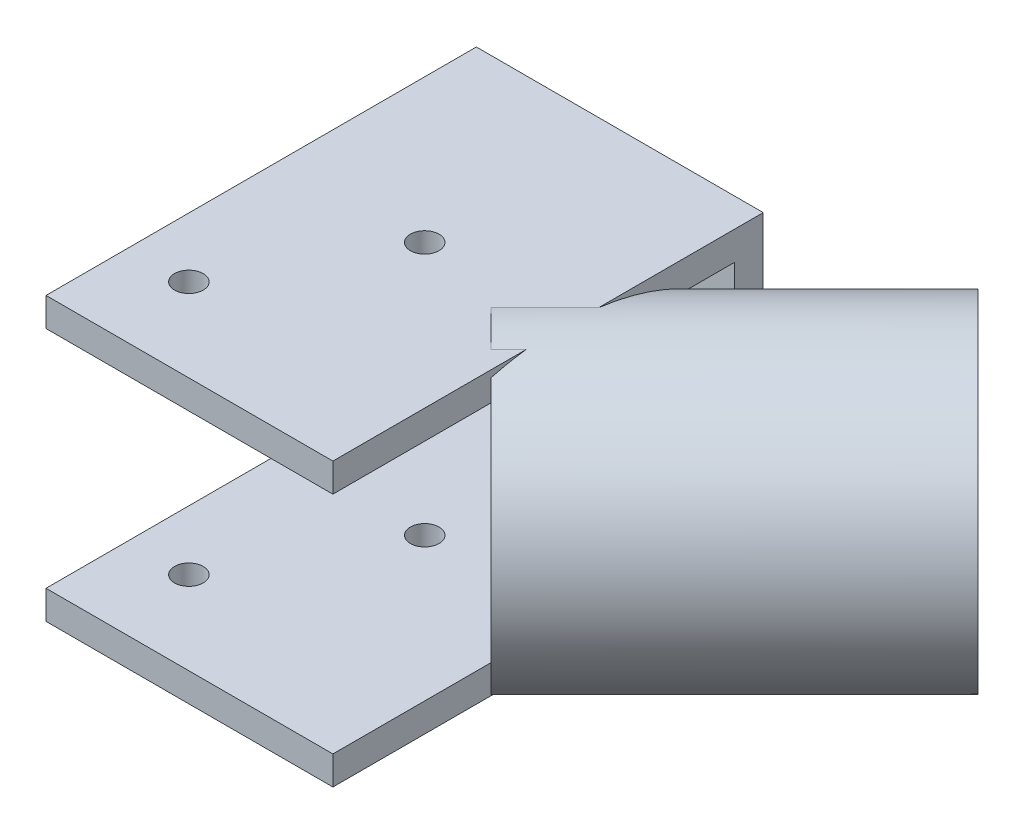
SolidWorks part; units mm, degrees
ref_plane "Plan de face" through (0, 0, 0) normal (0, 0, 1) x (1, 0, 0)
ref_plane "Plan de dessus" through (0, 0, 0) normal (0, 1, 0) x (1, 0, 0)
ref_plane "Plan de droite" through (0, 0, 0) normal (1, 0, 0) x (0, 0, -1)
sketch "Esquisse1" plane through (0, 0, 0) normal (0, 0, 1) x (1, 0, 0)
  line L0 (0, 24.6) -> (50, 24.6) construction
  line L1 (0, 0) -> (50, 0)
  line L2 (0, 0) -> (0, 49.2)
  line L3 (0, 49.2) -> (50, 49.2)
  line L4 (50, 0) -> (50, 49.2)
  dimension "D1" = 50
  dimension "D2" = 24.6
  dimension "D3" = 24.6
extrude "Boss.-Extru.1" add sketch "Esquisse1" along normal blind 5
sketch "Esquisse4" plane through (0, 0, 5) normal (0, 0, 1) x (1, 0, 0)
  line L0 (50, 0) -> (50, 49.2) construction
  line L1 (0, 49.2) -> (50, 49.2)
  line L2 (0, 49.2) -> (0, 44.2)
  line L3 (0, 44.2) -> (50, 44.2)
  line L4 (50, 49.2) -> (50, 44.2)
  line L6 (0, 0) -> (50, 0)
  line L7 (0, 0) -> (0, 5)
  line L8 (0, 5) -> (50, 5)
  line L9 (50, 0) -> (50, 5)
  dimension "D1" = 5
  dimension "D2" = 5
extrude "Boss.-Extru.3" add sketch "Esquisse4" along normal blind 70
sketch "Esquisse5" plane through (0, 0, 5) normal (0, 0, 1) x (1, 0, 0)
  line L0 (0, 5) -> (50, 44.2) construction
  line L1 (50, 5) -> (0, 44.2) construction
  line L3 (40.7, 8.9) -> (9.3, 8.9) construction
  line L4 (40.7, 8.9) -> (40.7, 40.3) construction
  line L5 (40.7, 40.3) -> (9.3, 40.3) construction
  line L6 (9.3, 8.9) -> (9.3, 40.3) construction
  line L7 (40.7, 8.9) -> (9.3, 40.3) construction
  line L8 (40.7, 40.3) -> (9.3, 8.9) construction
  circle A0 centre (25, 24.6) radius 10
  circle A5 centre (9.3, 8.9) radius 1.25
  circle A6 centre (40.7, 40.3) radius 1.25
  circle A7 centre (40.7, 8.9) radius 1.25
  circle A8 centre (9.3, 40.3) radius 1.25
  dimension "D1" = 20
  dimension "D2" = 31.4
  dimension "D3" = 31.4
  dimension "D4" = 2.5
  dimension "D5" = 2.5
  dimension "D6" = 2.5
  dimension "D7" = 2.5
extrude "Enlèv. mat.-Extru.1" cut sketch "Esquisse5" against normal through all
sketch "Esquisse6" plane through (0, 0, 0) normal (0, 0, -1) x (-1, 0, 0)
  circle A0 centre (-25, 24.6) radius 11
  dimension "D1" = 22
extrude "Enlèv. mat.-Extru.2" cut sketch "Esquisse6" against normal blind 2
sketch "Esquisse7" plane through (0, 0, 0) normal (0, -1, 0) x (1, 0, 0)
  line L0 (50, 75) -> (50, 0) construction
  line L1 (0, 0) -> (50, 0) construction
  circle A0 centre (25, 34) radius 2.5
  point P6 (25, 0)
  dimension "D1" = 5
  dimension "D2" = 25
  dimension "D3" = 34
extrude "Enlèv. mat.-Extru.3" cut sketch "Esquisse7" against normal through all both and the other way through all
sketch "Esquisse8" plane through (0, 0, 0) normal (0, -1, 0) x (1, 0, 0)
  circle A0 centre (10.4, 60.5) radius 2.5
  circle A1 centre (25, 34) radius 2.5 construction
  dimension "D1" = 5
  dimension "D2" = 14.6
  dimension "D3" = 26.5
extrude "Enlèv. mat.-Extru.4" cut sketch "Esquisse8" against normal through all
sketch "Esquisse9" plane through (0, 0, 0) normal (0, -1, 0) x (1, 0, 0)
  line L0 (0, 75) -> (50, 75) construction
  line L1 (50, 75) -> (50, 25) construction
  line L2 (50, 75) -> (50, 0) construction
  line L3 (0, 75) -> (85.1037, -10.1037) construction
  dimension "D1" = 50
ref_plane "Plan1" through (50, 5, 5) normal (-0.7071, 0, 0.7071) x (0.7071, 0, 0.7071)
sketch "Esquisse10" plane through (50, 5, 5) normal (-0.7071, 0, 0.7071) x (0.7071, 0, 0.7071)
  line L0 (0, 19.6) -> (30.6845, 19.6) construction
  line L1 (0, 0) -> (0, 39.2) construction
  circle A0 centre (21.2265, 19.6) radius 15
  circle A1 centre (21.2265, 19.6) radius 25
  dimension "D1" = 30
  dimension "D2" = 50
extrude "Boss.-Extru.4" add sketch "Esquisse10" along normal mid plane 60
sketch "Esquisse12" plane through (0, 5, 0) normal (0, 1, 0) x (1, 0, 0)
  line L0 (50, -5) -> (0, -5) construction
  line L1 (0, -75) -> (50, -75)
  line L2 (0, -75) -> (0, -5)
  line L3 (0, -5) -> (50, -5)
  line L4 (50, -75) -> (50, -5)
extrude "Enlèv. mat.-Extru.6" cut sketch "Esquisse12" along normal blind 39.2
